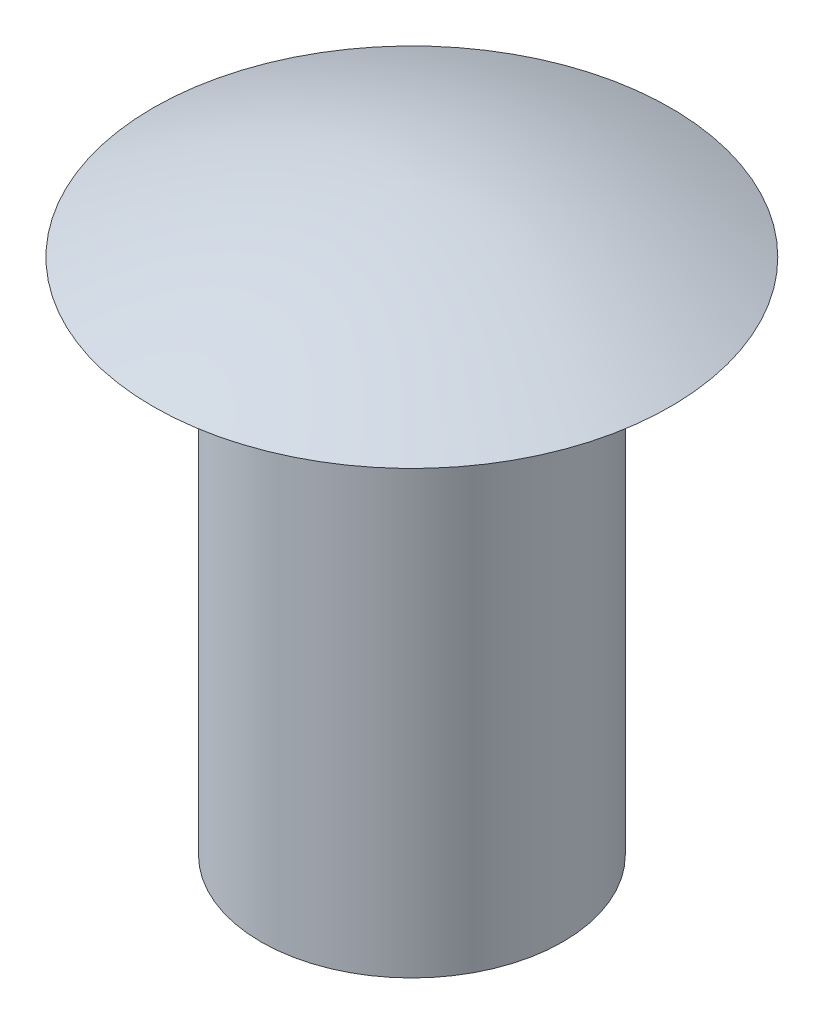
SolidWorks part; units mm, degrees
ref_plane "Front Plane" through (0, 0, 0) normal (0, 0, 1) x (1, 0, 0)
ref_plane "Top Plane" through (0, 0, 0) normal (0, 1, 0) x (1, 0, 0)
ref_plane "Right Plane" through (0, 0, 0) normal (1, 0, 0) x (0, 0, -1)
sketch "Sketch1" plane through (0, 0, 0) normal (0, 1, 0) x (1, 0, 0)
  circle A0 centre (0, 0) radius 1.75
  dimension "D1" = 3.5
extrude "Boss-Extrude1" add sketch "Sketch1" along normal blind 6
sketch "Sketch2" plane through (0, 0, 0) normal (0, 0, 1) x (1, 0, 0)
  line L0 (0, 6) -> (-3, 6)
  line L1 (1.75, 6) -> (-1.75, 6) construction
  line L2 (0, 6.7969) -> (0, 6)
  spline S0 degree 3 poles (-3, 6) (-2.0625, 6.4345) (-1.1446, 6.7659) (0, 6.7969) knots 0 0 0 0 1 1 1 1
  dimension "D1" = 3
revolve "Revolve1" add sketch "Sketch2" angle 360 about L2
